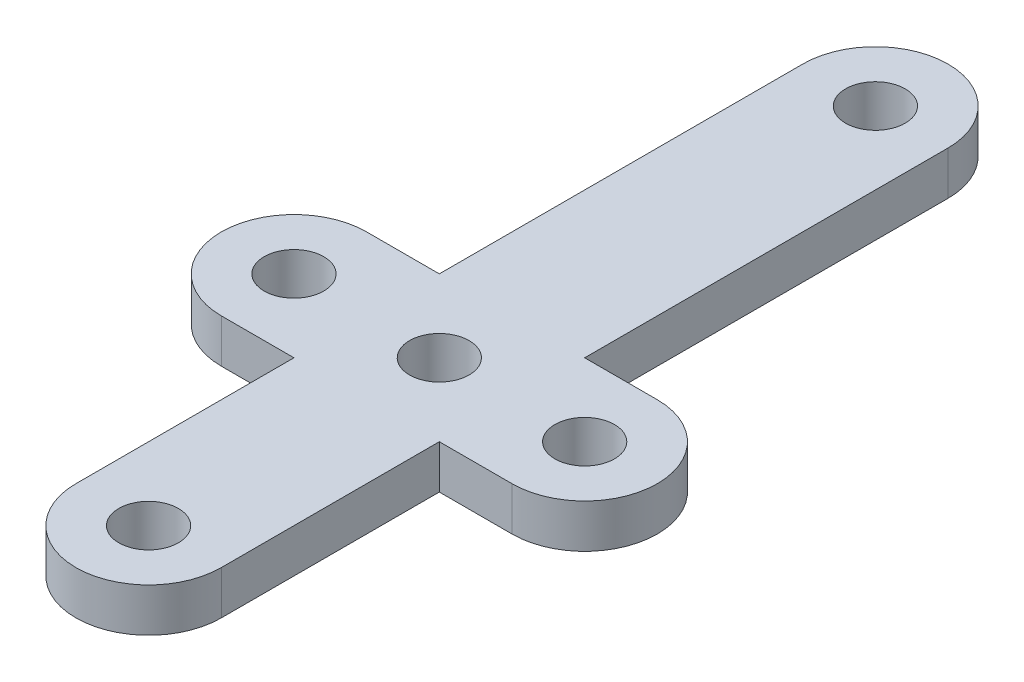
SolidWorks part; units mm, degrees
ref_plane "Front Plane" through (0, 0, 0) normal (0, 0, 1) x (1, 0, 0)
ref_plane "Top Plane" through (0, 0, 0) normal (0, 1, 0) x (1, 0, 0)
ref_plane "Right Plane" through (0, 0, 0) normal (1, 0, 0) x (0, 0, -1)
sketch "Sketch1" plane through (0, 0, 0) normal (0, 1, 0) x (1, 0, 0)
  line L0 (-10, -5) -> (-7.95, -5) construction
  line L1 (-10, 0) -> (-5, 0)
  line L2 (-10, -10) -> (-5, -10)
  line L3 (0, -20.5263) -> (0, 20.5263) construction
  line L4 (0, -13.9484) -> (0, -22.95) construction
  line L5 (-5, -25) -> (-5, -10)
  line L6 (5, -25) -> (5, -10)
  line L7 (-16.5, 0) -> (16.5, 0) construction
  line L8 (-5, 0) -> (-5, 25)
  line L9 (5, 0) -> (10, 0)
  line L10 (0, 22.95) -> (0, 25) construction
  line L11 (-2.05, -5) -> (2.05, -5) construction
  line L12 (7.95, -5) -> (10, -5) construction
  line L13 (5, 0) -> (5, 25)
  line L14 (5, -10) -> (10, -10)
  line L15 (0, -7.05) -> (0, -2.95) construction
  arc A0 (-10, 0) -> (-10, -10) centre (-10, -5) ccw
  arc A1 (10, -10) -> (10, 0) centre (10, -5) ccw
  circle A2 centre (10, -5) radius 2.05
  circle A3 centre (-10, -5) radius 2.05
  circle A4 centre (0, -5) radius 2.05
  circle A7 centre (0, 25) radius 2.05
  circle A8 centre (0, -25) radius 2.05
  arc A9 (-5, -25) -> (5, -25) centre (0, -25) ccw
  arc A10 (-5, 25) -> (5, 25) centre (0, 25) cw
  point P2 (0, 0)
  point P18 (0, -5)
  dimension "D3" = 4.1
  dimension "D4" = 4.1
  dimension "D7" = 4.1
  dimension "D8" = 20
  dimension "D10" = 10
  dimension "D6" = 5
  dimension "D11" = 10
  dimension "D13" = 5
  dimension "D9" = 30
  dimension "D1" = 10
  dimension "D2" = 20
  dimension "D5" = 10
extrude "Boss-Extrude1" add sketch "Sketch1" along normal mid plane 3
